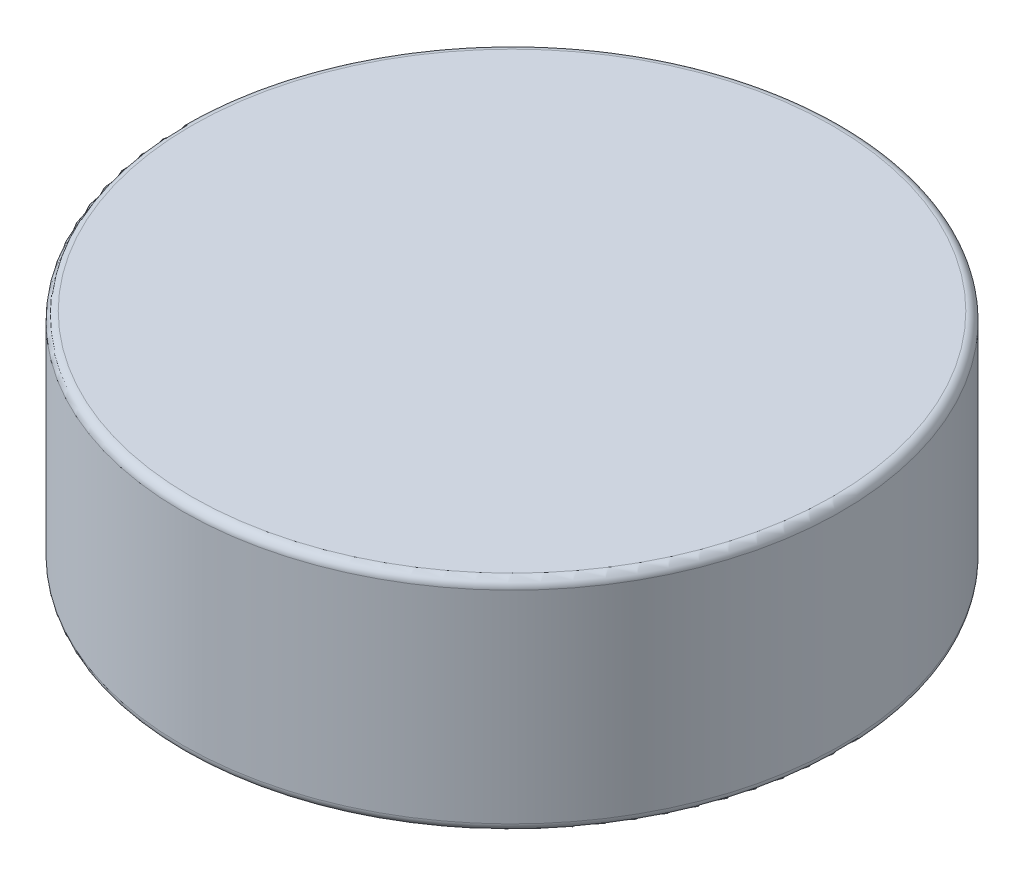
SolidWorks part; units mm, degrees
material "EPICHLOROHYDRINE"
ref_plane "Plan de face" through (0, 0, 0) normal (0, 0, 1) x (1, 0, 0)
ref_plane "Plan de dessus" through (0, 0, 0) normal (0, 1, 0) x (1, 0, 0)
ref_plane "Plan de droite" through (0, 0, 0) normal (1, 0, 0) x (0, 0, -1)
sketch "Esquisse1" plane through (0, 0, 0) normal (0, 1, 0) x (1, 0, 0)
  circle A0 centre (0, 0) radius 38.1
  dimension "D1" = 76.2
extrude "Boss.-Extru.1" add sketch "Esquisse1" along normal mid plane 25.4
fillet "Congé1" radius 1 2 edges at (0, -12.7, 38.1) (0, 12.7, 38.1)
